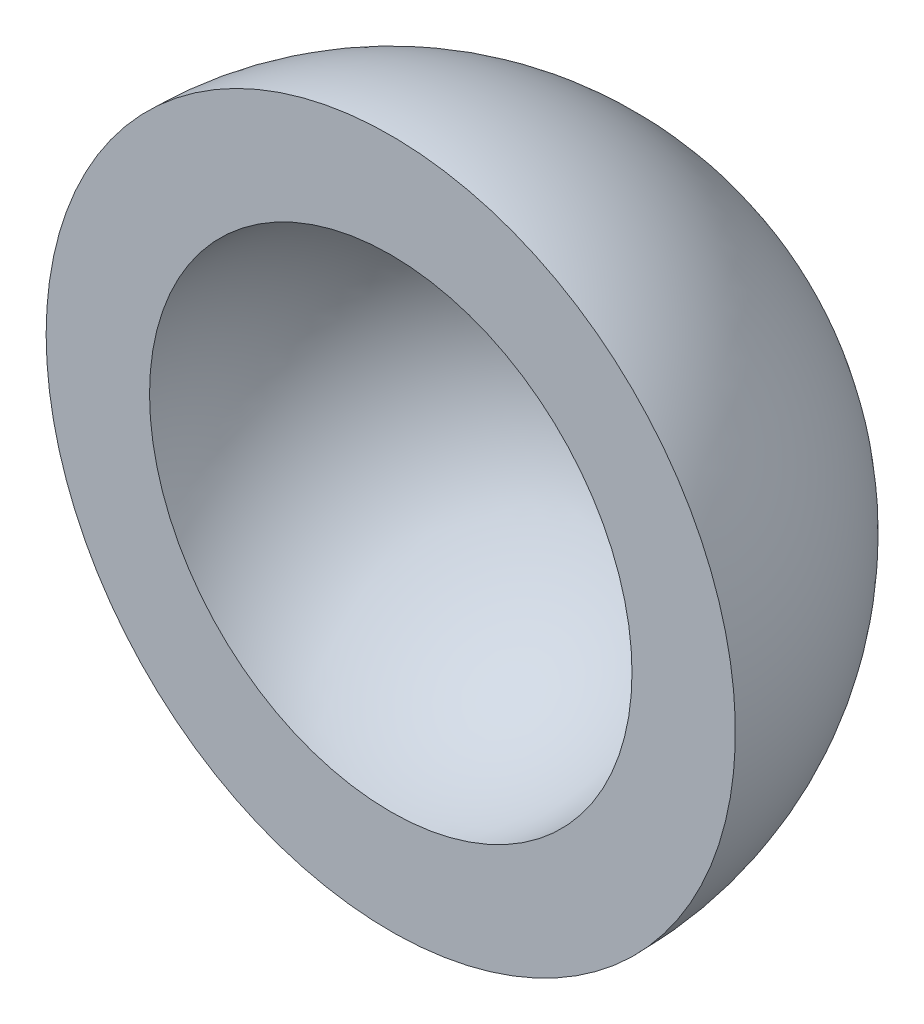
SolidWorks part; units mm, degrees
ref_plane "正面" through (0, 0, 0) normal (0, 0, 1) x (1, 0, 0)
ref_plane "平面" through (0, 0, 0) normal (0, 1, 0) x (1, 0, 0)
ref_plane "右側面" through (0, 0, 0) normal (1, 0, 0) x (0, 0, -1)
sketch "ｽｹｯﾁ1" plane through (0, 0, 0) normal (0, 0, 1) x (1, 0, 0)
  line L0 (0, 100) -> (0, -100)
  arc A0 (0, 100) -> (0, -100) centre (0, 0) ccw
  arc A1 (0, 70) -> (0, -70) centre (0, 0) ccw
  dimension "D1" = 100
  dimension "D2" = 70
revolve "回転1" add sketch "ｽｹｯﾁ1" angle 180 about L0
